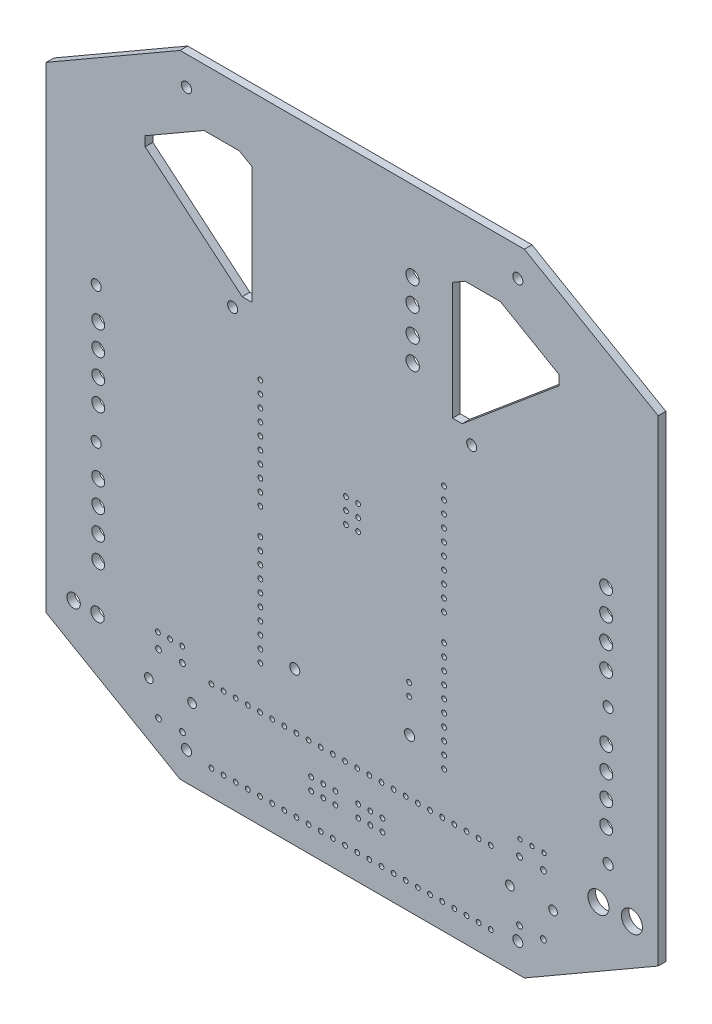
SolidWorks part; units mm, degrees
ref_plane "Front Plane" through (0, 0, 0) normal (0, 0, 1) x (1, 0, 0)
ref_plane "Top Plane" through (0, 0, 0) normal (0, 1, 0) x (1, 0, 0)
ref_plane "Right Plane" through (0, 0, 0) normal (1, 0, 0) x (0, 0, -1)
sketch "Model" plane through (0, 0, 0) normal (0, 0, 1) x (1, 0, 0)
  line L0 (-64, -49.8342) -> (-36, -66)
  line L1 (-36, -66) -> (36, -66)
  line L2 (36, -66) -> (64, -49.8342)
  line L3 (64, -49.8342) -> (64, 49.8342)
  line L4 (64, 49.8342) -> (36, 66)
  line L5 (36, 66) -> (-36, 66)
  line L6 (-36, 66) -> (-64, 49.8342)
  line L7 (-64, 49.8342) -> (-64, -49.8342)
  line L8 (-43.2818, 44.9091) -> (-23, 27.8907)
  line L9 (-23, 27.8907) -> (-21, 27.8907)
  line L10 (-21, 27.8907) -> (-21, 52.5)
  line L11 (-21, 52.5) -> (-23.5981, 54)
  line L12 (-23.5981, 54) -> (-31, 54)
  line L13 (-31, 54) -> (-43.2818, 46.9091)
  line L14 (-43.2818, 46.9091) -> (-43.2818, 44.9091)
  line L15 (21, 27.8907) -> (23, 27.8907)
  line L16 (23, 27.8907) -> (43.2818, 44.9091)
  line L17 (43.2818, 44.9091) -> (43.2818, 46.9091)
  line L18 (43.2818, 46.9091) -> (31, 54)
  line L19 (31, 54) -> (23.5981, 54)
  line L20 (23.5981, 54) -> (21, 52.5)
  line L21 (21, 52.5) -> (21, 27.8907)
  circle A0 centre (58.5, -44.5) radius 2.2
  circle A1 centre (51.5, -44.5) radius 2.2
  circle A2 centre (12.65, 38.66) radius 1.4
  circle A3 centre (-58.26, -44.77) radius 1.4
  circle A4 centre (12.63, 44.24) radius 1.4
  circle A5 centre (12.63, 49.24) radius 1.4
  circle A6 centre (-53.26, -44.77) radius 1.4
  circle A7 centre (12.65, 33.66) radius 1.4
  circle A8 centre (53.11, 13.33) radius 1.35
  circle A9 centre (-53.11, -6.73) radius 1.35
  circle A10 centre (-53.11, -1.73) radius 1.35
  circle A11 centre (53.13, -15.08) radius 1.35
  circle A12 centre (-53.11, 3.27) radius 1.35
  circle A13 centre (-53.11, 8.27) radius 1.35
  circle A14 centre (53.11, 8.33) radius 1.35
  circle A15 centre (53.11, 3.33) radius 1.35
  circle A16 centre (53.11, -1.67) radius 1.35
  circle A17 centre (-53.11, -35.13) radius 1.35
  circle A18 centre (-53.11, -30.13) radius 1.35
  circle A19 centre (-53.11, -20.13) radius 1.35
  circle A20 centre (53.13, -20.08) radius 1.35
  circle A21 centre (53.13, -25.08) radius 1.35
  circle A22 centre (53.13, -30.08) radius 1.35
  circle A23 centre (-53.11, -25.13) radius 1.35
  circle A24 centre (-12, -34) radius 1.05
  circle A25 centre (12, -34) radius 1.05
  circle A26 centre (-25, 25) radius 1.05
  circle A27 centre (25, 25) radius 1.05
  circle A28 centre (-53.53, 14.75) radius 1.05
  circle A29 centre (53.53, -36.56) radius 1.05
  circle A30 centre (53.53, -8.15) radius 1.05
  circle A31 centre (-34.64, -60) radius 1.05
  circle A32 centre (34.64, -60) radius 1.05
  circle A33 centre (-34.65, 60) radius 1.05
  circle A34 centre (34.64, 60) radius 1.05
  circle A35 centre (-53.54, -13.67) radius 1.05
  circle A36 centre (-33.4934, -50.9484) radius 0.9017
  circle A37 centre (-42.5104, -50.9484) radius 0.9017
  circle A38 centre (32.9896, -50.7484) radius 0.9017
  circle A39 centre (42.0066, -50.7484) radius 0.9017
  circle A40 centre (40, -44.5) radius 0.5969
  circle A41 centre (-35.5, -44.7) radius 0.5969
  circle A42 centre (34.9962, -44.5) radius 0.5969
  circle A43 centre (-40.5038, -44.7) radius 0.5969
  circle A44 centre (-40.5038, -57.1968) radius 0.5969
  circle A45 centre (-35.5, -57.1968) radius 0.5969
  circle A46 centre (40, -56.9968) radius 0.5969
  circle A47 centre (34.9962, -56.9968) radius 0.5969
  circle A48 centre (6.12, -60.72) radius 0.5
  circle A49 centre (8.66, -60.72) radius 0.5
  circle A50 centre (11.2, -60.72) radius 0.5
  circle A51 centre (13.74, -60.72) radius 0.5
  circle A52 centre (16.28, -60.72) radius 0.5
  circle A53 centre (18.82, -60.72) radius 0.5
  circle A54 centre (21.36, -60.72) radius 0.5
  circle A55 centre (-6.58, -45.48) radius 0.5
  circle A56 centre (-11.66, -45.48) radius 0.5
  circle A57 centre (-14.2, -45.48) radius 0.5
  circle A58 centre (-16.74, -45.48) radius 0.5
  circle A59 centre (-19.28, -45.48) radius 0.5
  circle A60 centre (-21.82, -45.48) radius 0.5
  circle A61 centre (-24.36, -45.48) radius 0.5
  circle A62 centre (-26.9, -45.48) radius 0.5
  circle A63 centre (-29.44, -45.48) radius 0.5
  circle A64 centre (-9.12, -60.72) radius 0.5
  circle A65 centre (-11.66, -60.72) radius 0.5
  circle A66 centre (-14.2, -60.72) radius 0.5
  circle A67 centre (-16.74, -60.72) radius 0.5
  circle A68 centre (-19.28, -60.72) radius 0.5
  circle A69 centre (-21.82, -60.72) radius 0.5
  circle A70 centre (-24.36, -60.72) radius 0.5
  circle A71 centre (-26.9, -60.72) radius 0.5
  circle A72 centre (-29.44, -60.72) radius 0.5
  circle A73 centre (-9.12, -45.48) radius 0.5
  circle A74 centre (-6.58, -60.72) radius 0.5
  circle A75 centre (1.24, 2.54) radius 0.5
  circle A76 centre (1.24, 0) radius 0.5
  circle A77 centre (1.24, -2.54) radius 0.5
  circle A78 centre (-1.3, -2.54) radius 0.5
  circle A79 centre (-1.3, 0) radius 0.5
  circle A80 centre (-1.3, 2.54) radius 0.5
  circle A81 centre (3.58, -60.72) radius 0.5
  circle A82 centre (26.44, -60.72) radius 0.5
  circle A83 centre (11.9, -27.04) radius 0.5
  circle A84 centre (11.9, -24.5) radius 0.5
  circle A85 centre (-35.55, -41.65) radius 0.5
  circle A86 centre (-38.09, -41.65) radius 0.5
  circle A87 centre (-40.63, -41.65) radius 0.5
  circle A88 centre (28.98, -60.72) radius 0.5
  circle A89 centre (23.9, -60.72) radius 0.5
  circle A90 centre (-4.04, -60.72) radius 0.5
  circle A91 centre (-4.04, -45.48) radius 0.5
  circle A92 centre (26.44, -45.48) radius 0.5
  circle A93 centre (-19.2, 14.73) radius 0.5
  circle A94 centre (-19.2, 12.19) radius 0.5
  circle A95 centre (-19.2, 9.65) radius 0.5
  circle A96 centre (-19.2, 7.11) radius 0.5
  circle A97 centre (-19.2, 4.57) radius 0.5
  circle A98 centre (-19.2, 2.03) radius 0.5
  circle A99 centre (-19.2, -0.51) radius 0.5
  circle A100 centre (-19.2, -3.05) radius 0.5
  circle A101 centre (-19.2, -5.59) radius 0.5
  circle A102 centre (-19.2, -8.13) radius 0.5
  circle A103 centre (23.9, -45.48) radius 0.5
  circle A104 centre (21.36, -45.48) radius 0.5
  circle A105 centre (18.82, -45.48) radius 0.5
  circle A106 centre (16.28, -45.48) radius 0.5
  circle A107 centre (19.2, -8.13) radius 0.5
  circle A108 centre (19.2, -5.59) radius 0.5
  circle A109 centre (19.2, -3.05) radius 0.5
  circle A110 centre (19.2, -0.51) radius 0.5
  circle A111 centre (19.2, 2.03) radius 0.5
  circle A112 centre (19.2, 4.57) radius 0.5
  circle A113 centre (19.2, 7.11) radius 0.5
  circle A114 centre (19.2, 9.65) radius 0.5
  circle A115 centre (19.2, 12.19) radius 0.5
  circle A116 centre (19.2, 14.73) radius 0.5
  circle A117 centre (13.74, -45.48) radius 0.5
  circle A118 centre (11.2, -45.48) radius 0.5
  circle A119 centre (8.66, -45.48) radius 0.5
  circle A120 centre (6.12, -45.48) radius 0.5
  circle A121 centre (-19.2, -13.67) radius 0.5
  circle A122 centre (-19.2, -16.21) radius 0.5
  circle A123 centre (-19.2, -18.75) radius 0.5
  circle A124 centre (-19.2, -21.29) radius 0.5
  circle A125 centre (-19.2, -23.83) radius 0.5
  circle A126 centre (-19.2, -26.37) radius 0.5
  circle A127 centre (-19.2, -28.91) radius 0.5
  circle A128 centre (-19.2, -31.45) radius 0.5
  circle A129 centre (-19.2, -33.99) radius 0.5
  circle A130 centre (-19.2, -36.53) radius 0.5
  circle A131 centre (28.98, -45.48) radius 0.5
  circle A132 centre (3.58, -45.48) radius 0.5
  circle A133 centre (1.04, -45.48) radius 0.5
  circle A134 centre (-1.5, -45.48) radius 0.5
  circle A135 centre (19.22, -36.54) radius 0.5
  circle A136 centre (19.22, -34) radius 0.5
  circle A137 centre (19.22, -31.46) radius 0.5
  circle A138 centre (19.22, -28.92) radius 0.5
  circle A139 centre (19.22, -26.38) radius 0.5
  circle A140 centre (19.22, -23.84) radius 0.5
  circle A141 centre (19.22, -21.3) radius 0.5
  circle A142 centre (19.22, -18.76) radius 0.5
  circle A143 centre (19.22, -16.22) radius 0.5
  circle A144 centre (19.22, -13.68) radius 0.5
  circle A145 centre (-1.5, -60.72) radius 0.5
  circle A146 centre (1.04, -60.72) radius 0.5
  circle A147 centre (1.25, -51.86) radius 0.5
  circle A148 centre (3.79, -51.86) radius 0.5
  circle A149 centre (6.33, -51.86) radius 0.5
  circle A150 centre (6.33, -54.4) radius 0.5
  circle A151 centre (3.79, -54.4) radius 0.5
  circle A152 centre (1.25, -54.4) radius 0.5
  circle A153 centre (-8.59, -51.86) radius 0.5
  circle A154 centre (-6.05, -51.86) radius 0.5
  circle A155 centre (-3.51, -51.86) radius 0.5
  circle A156 centre (-3.51, -54.4) radius 0.5
  circle A157 centre (-6.05, -54.4) radius 0.5
  circle A158 centre (-8.59, -54.4) radius 0.5
  circle A159 centre (35.1, -41.3) radius 0.4445
  circle A160 centre (40.1038, -41.3) radius 0.4445
  circle A161 centre (37.5892, -41.3) radius 0.4445
extrude "Boss-Extrude1" add sketch "Model" along normal blind 1.6
